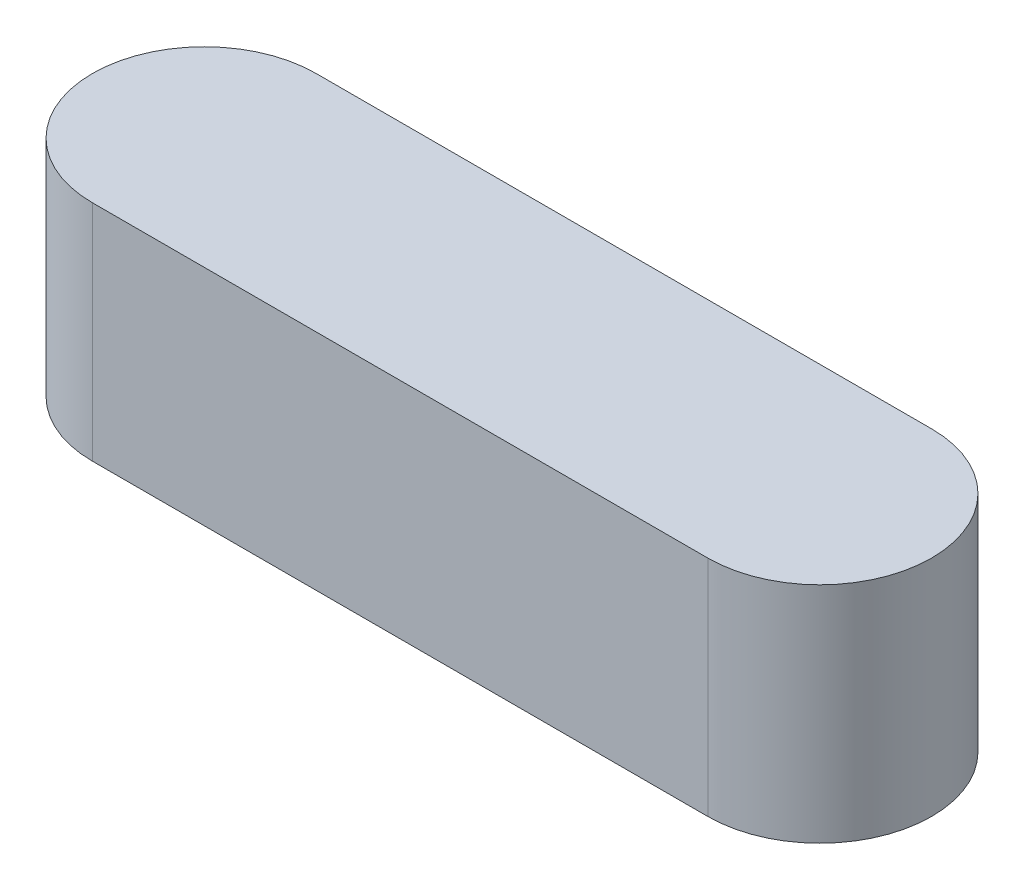
SolidWorks part; units mm, degrees
ref_plane "Front Plane" through (0, 0, 0) normal (0, 0, 1) x (1, 0, 0)
ref_plane "Top Plane" through (0, 0, 0) normal (0, 1, 0) x (1, 0, 0)
ref_plane "Right Plane" through (0, 0, 0) normal (1, 0, 0) x (0, 0, -1)
sketch "Sketch1" plane through (0, 0, 0) normal (0, 1, 0) x (1, 0, 0)
  line L0 (-27.5, 0) -> (27.5, 0) construction
  line L1 (-27.5, 10) -> (27.5, 10)
  line L2 (-27.5, -10) -> (27.5, -10)
  arc A0 (-27.5, 10) -> (-27.5, -10) centre (-27.5, 0) ccw
  arc A1 (27.5, -10) -> (27.5, 10) centre (27.5, 0) ccw
  point P3 (0, 0)
  dimension "D1" = 10
  dimension "D2" = 55
extrude "Boss-Extrude1" add sketch "Sketch1" along normal blind 20
equation "\"TibiaLength\" = 55mm"
equation "\"TibiaRadius\" = 10mm"
equation "\"TibiaThickness\" = 20mm"
equation "\"D1@Sketch1\"= \"TibiaRadius\""
equation "\"D2@Sketch1\" = \"TibiaLength\""
equation "\"D1@Boss-Extrude1\"= \"TibiaThickness\""
